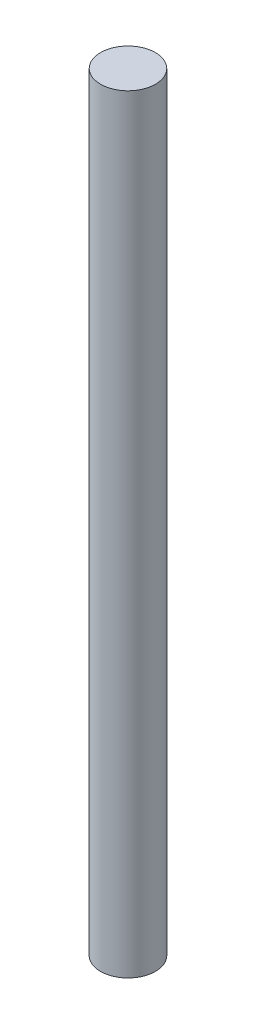
SolidWorks part; units mm, degrees
ref_plane "Alzado" through (0, 0, 0) normal (0, 0, 1) x (1, 0, 0)
ref_plane "Planta" through (0, 0, 0) normal (0, 1, 0) x (1, 0, 0)
ref_plane "Vista lateral" through (0, 0, 0) normal (1, 0, 0) x (0, 0, -1)
sketch "Croquis1" plane through (0, 0, 0) normal (0, 1, 0) x (1, 0, 0)
  circle A0 centre (0, 0) radius 4
  dimension "D1" = 8
extrude "Saliente-Extruir1" add sketch "Croquis1" along normal blind 112
